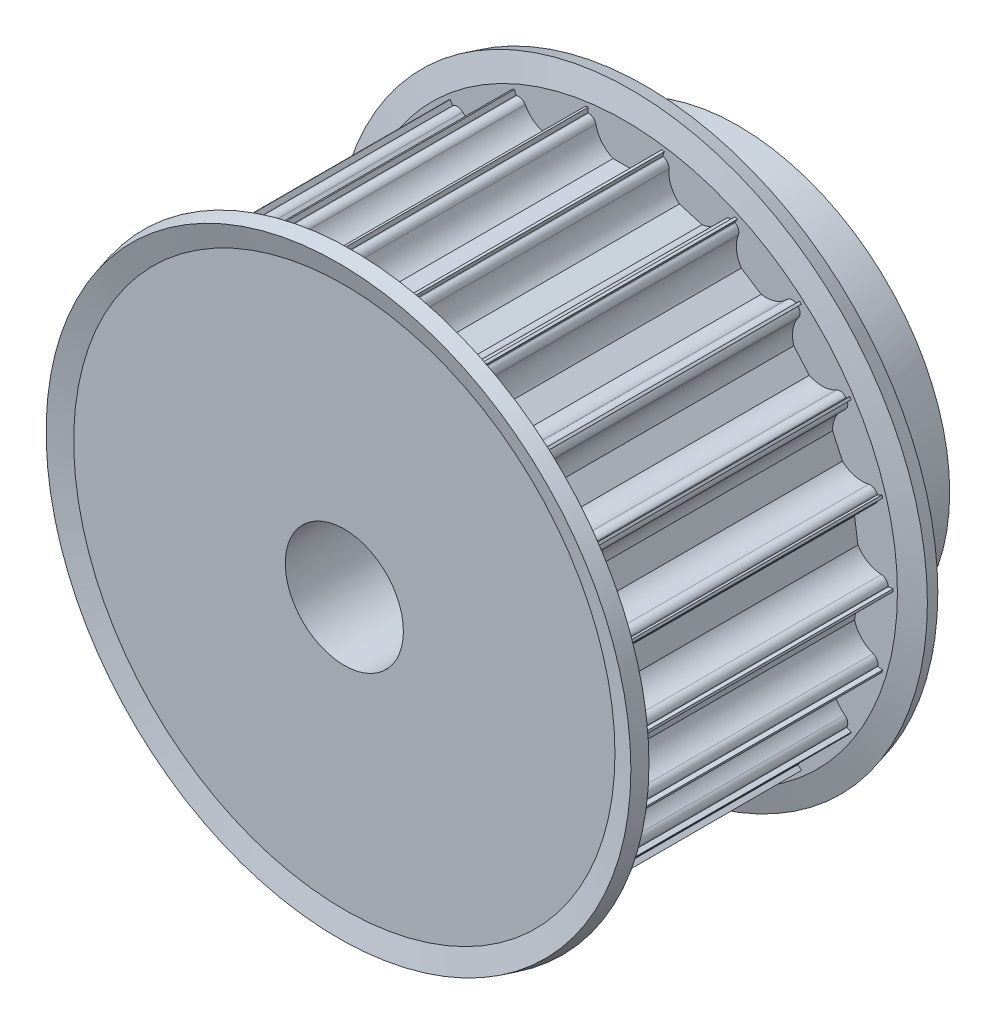
SolidWorks part; units mm, degrees
ref_plane "Front Plane" through (0, 0, 0) normal (0, 0, 1) x (1, 0, 0)
ref_plane "Top Plane" through (0, 0, 0) normal (0, 1, 0) x (1, 0, 0)
ref_plane "Right Plane" through (0, 0, 0) normal (1, 0, 0) x (0, 0, -1)
ref_axis "Axis1" through (0, 0, 55) along (0, 0, -1)
sketch "Sketch1" plane through (0, 0, 0) normal (1, 0, 0) x (0, 0, -1)
  line L0 (0, 6) -> (0, 27.25)
  line L1 (0, 27.25) -> (30, 27.25)
  line L2 (30, 27.25) -> (30, 21.5)
  line L3 (30, 21.5) -> (40, 21.5)
  line L4 (40, 21.5) -> (40, 6)
  line L5 (40, 6) -> (0, 6)
  line L6 (-55, 0) -> (55, 0) construction
  dimension "D1" = 6
  dimension "D2" = 21.25
  dimension "D3" = 30
  dimension "D4" = 10
  dimension "D5" = 15.5
revolve "Revolve1" add sketch "Sketch1" angle 360 about axis through (0, 0, 55) along (0, 0, -1)
sketch "Sketch2" plane through (0, 0, 0) normal (0, 0, 1) x (1, 0, 0)
  line L0 (3.6742, 26.5) -> (3.75, 26.5)
  line L1 (-3.75, 28.5) -> (3.75, 28.5)
  line L2 (-3.75, 28.5) -> (-3.75, 26.5)
  line L3 (-3.75, 26.5) -> (-3.6742, 26.5)
  line L4 (3.75, 28.5) -> (3.75, 26.5)
  line L5 (1.199, 23.75) -> (-1.199, 23.75)
  arc A0 (-2.9394, 25.9) -> (-1.199, 23.75) centre (0, 26.5) ccw
  arc A1 (-2.9394, 25.9) -> (-3.6742, 26.5) centre (-3.6742, 25.75) ccw
  arc A2 (2.9394, 25.9) -> (3.6742, 26.5) centre (3.6742, 25.75) cw
  arc A3 (1.199, 23.75) -> (2.9394, 25.9) centre (0, 26.5) ccw
  dimension "D1" = 3
  dimension "D4" = 26.5
  dimension "D5" = 0.75
  dimension "D6" = 0.75
  dimension "D2" = 2
  dimension "D3" = 7.5
  dimension "D7" = 2.75
extrude "Cut-Extrude1" cut sketch "Sketch2" against normal through all
pattern_circular "CirPattern1" count 22 over 360 about axis through (0, 0, 0) along (0, 0, 1) of "Cut-Extrude1"
sketch "Sketch3" plane through (0, 0, 0) normal (1, 0, 0) x (0, 0, -1)
  line L0 (0, 25.679) -> (0, 23.1257) construction
  line L1 (0, 22.6907) -> (1.5, 22.6907)
  line L2 (0, 22.6907) -> (0, 27.6907)
  line L3 (0, 27.6907) -> (1.5, 27.6907) construction
  line L4 (1.5, 22.6907) -> (1.5, 27.6907)
  line L6 (1.5, 27.6907) -> (0.0511, 27.3025) construction
  line L7 (1.5, 27.6907) -> (0.8569, 30.0907)
  line L8 (0.0511, 27.3025) -> (-0.592, 29.7025)
  line L9 (0.8569, 30.0907) -> (-0.592, 29.7025)
  line L10 (30, 26.9907) -> (0, 26.9907) construction
  line L11 (15, 26.9539) -> (15, 32.6443) construction
  line L12 (0, 26.9539) -> (30, 26.9539) construction
  line L13 (28.5, 27.6907) -> (29.9489, 27.3025) construction
  line L14 (30, 27.6907) -> (28.5, 27.6907) construction
  line L15 (29.1431, 30.0907) -> (30.592, 29.7025)
  line L16 (29.9489, 27.3025) -> (30.592, 29.7025)
  line L17 (28.5, 27.6907) -> (29.1431, 30.0907)
  line L18 (28.5, 22.6907) -> (28.5, 27.6907)
  line L19 (30, 22.6907) -> (30, 27.6907)
  line L20 (30, 22.6907) -> (28.5, 22.6907)
  dimension "D1" = 1.5
  dimension "D2" = 5
  dimension "D3" = 165
  dimension "D4" = 1.5
  dimension "D5" = 0.7
  dimension "D6" = 2.4
revolve "Revolve2" add sketch "Sketch3" angle 360 about axis through (0, 0, 55) along (0, 0, -1)
